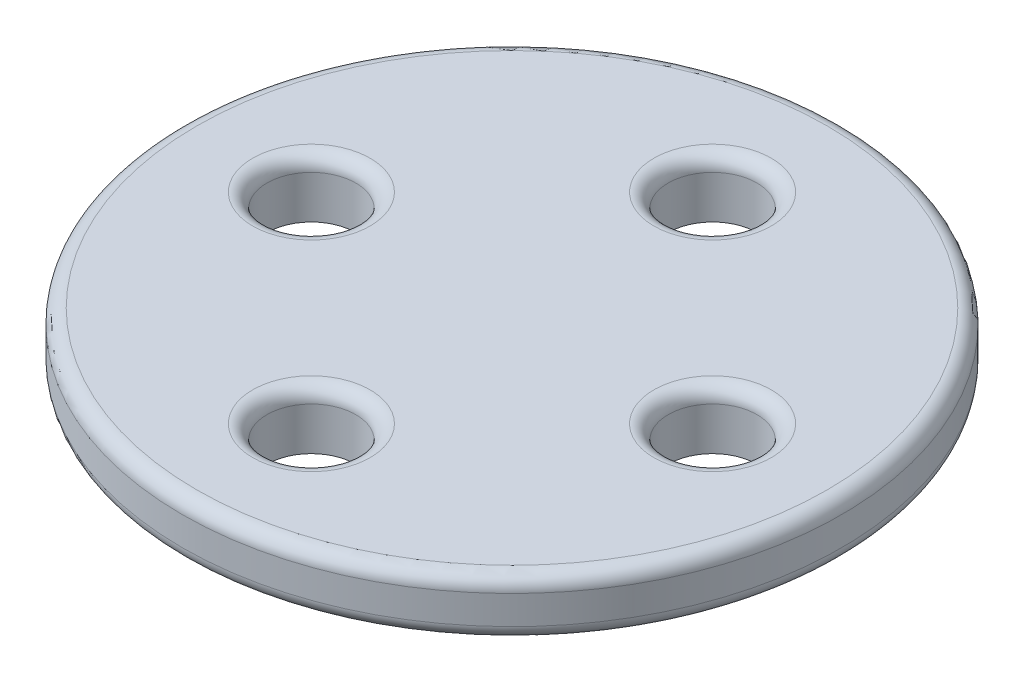
SolidWorks part; units mm, degrees
ref_plane "Front Plane" through (0, 0, 0) normal (0, 0, 1) x (1, 0, 0)
ref_plane "Top Plane" through (0, 0, 0) normal (0, 1, 0) x (1, 0, 0)
ref_plane "Right Plane" through (0, 0, 0) normal (1, 0, 0) x (0, 0, -1)
sketch "Sketch1" plane through (0, 0, 0) normal (0, 1, 0) x (1, 0, 0)
  line L0 (0, 7) -> (0, 0) construction
  circle A0 centre (0, 0) radius 11.5
  circle A1 centre (0, 7) radius 1.55
  circle A2 centre (7, 0) radius 1.55
  circle A3 centre (0, -7) radius 1.55
  circle A4 centre (-7, 0) radius 1.55
  point P14 (0, 0)
  dimension "D1" = 23
  dimension "D2" = 3.1
  dimension "D3" = 7
  dimension "D4" = 4
extrude "Boss-Extrude1" add sketch "Sketch1" along normal blind 2
fillet "Fillet1" radius 0.5 6 edges at (-7, 2, 1.55) (7, 2, 1.55) (0, 2, 11.5) (0, 2, -5.45) (0, 2, 8.55) (0, 0, 11.5)
sketch "Sketch2" [suppressed] plane through (0, 2, 0) normal (0, 1, 0) x (1, 0, 0)
  line L0 (-2.4749, -2.4749) -> (2.4749, 2.4749) construction
  line L3 (-4.2426, -0.7071) -> (0.7071, 4.2426) construction
  line L4 (-0.7071, -4.2426) -> (4.2426, 0.7071) construction
  line L5 (0, 0) -> (23.072, 0) construction
  line L6 (-6.364, -2.1213) -> (-2.1213, -6.364) construction
  line L7 (-2.1213, -6.364) -> (6.364, 2.1213) construction
  line L8 (6.364, 2.1213) -> (2.1213, 6.364) construction
  line L9 (2.1213, 6.364) -> (-6.364, -2.1213) construction
  line L10 (-6.364, -2.1213) -> (6.364, 2.1213) construction
  line L11 (2.1213, 6.364) -> (6.364, 2.1213)
  line L12 (6.364, 2.1213) -> (4.9497, 0.7071)
  line L13 (2.1213, 6.364) -> (0.7071, 4.9497)
  line L14 (-6.364, -2.1213) -> (-4.9497, -0.7071)
  line L15 (-6.364, -2.1213) -> (-2.1213, -6.364)
  line L16 (-2.1213, -6.364) -> (-0.7071, -4.9497)
  circle A0 centre (-7, 0) radius 2.75 construction
  circle A1 centre (0, 7) radius 2.75 construction
  circle A2 centre (7, 0) radius 2.75 construction
  circle A3 centre (0, -7) radius 2.75 construction
  arc A6 (-4.2426, -0.7071) -> (-0.7071, -4.2426) centre (-2.4749, -2.4749) ccw construction
  arc A7 (4.2426, 0.7071) -> (0.7071, 4.2426) centre (2.4749, 2.4749) ccw construction
  circle A8 centre (0, 0) radius 5 construction
  arc A10 (-0.7071, -4.9497) -> (4.9497, 0.7071) centre (0, 0) ccw
  arc A12 (0.7071, 4.9497) -> (-4.9497, -0.7071) centre (0, 0) ccw
  point P13 (0, 0)
  dimension "D1" = 5.5
  dimension "D2" = 12
  dimension "D3" = 5
  dimension "D7" = 10
  dimension "D4" = 45
  dimension "D5" = 6
  dimension "D6" = 12
extrude "Cable hole" [suppressed] cut sketch "Sketch2" against normal through all
fillet "Fillet2" [suppressed] radius 1
